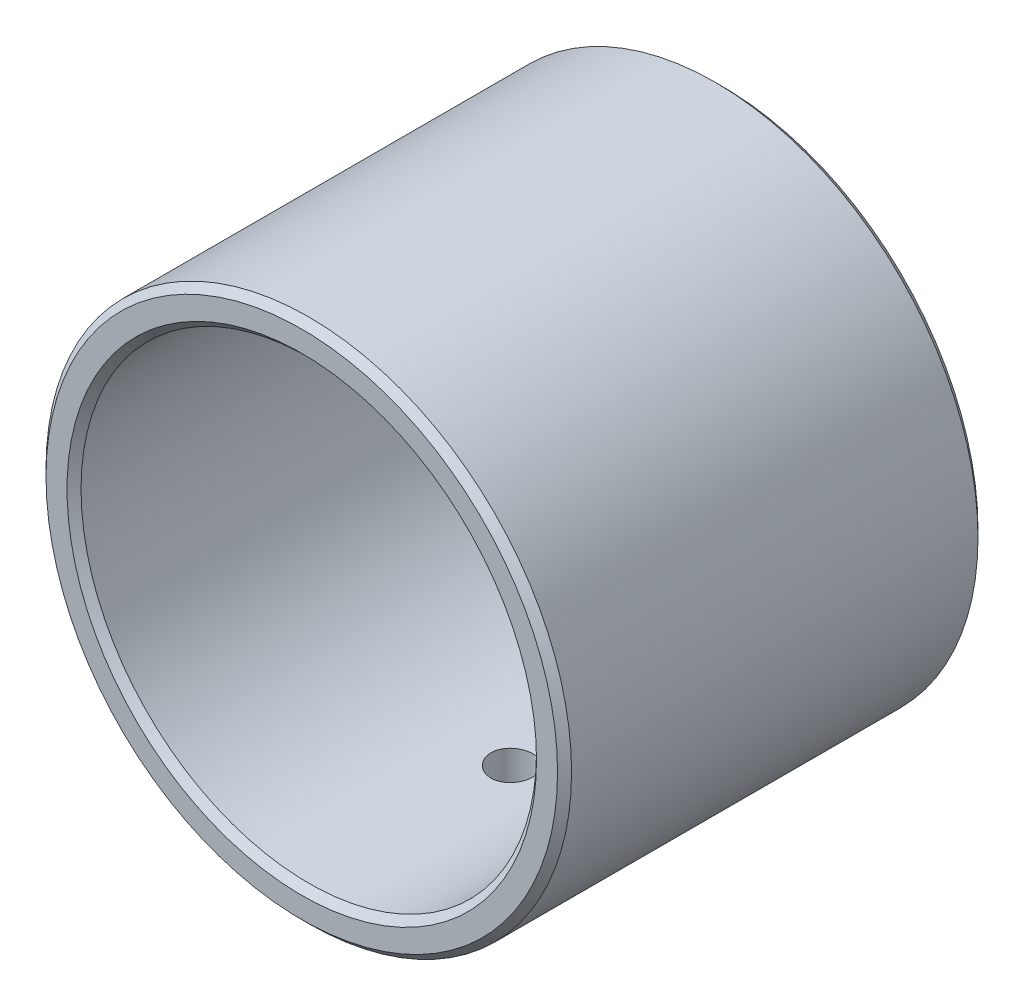
SolidWorks part; units mm, degrees
ref_plane "前视基准面" through (0, 0, 0) normal (0, 0, 1) x (1, 0, 0)
ref_plane "上视基准面" through (0, 0, 0) normal (0, 1, 0) x (1, 0, 0)
ref_plane "右视基准面" through (0, 0, 0) normal (1, 0, 0) x (0, 0, -1)
sketch "草图1" plane through (0, 0, 0) normal (0, 0, 1) x (1, 0, 0)
  circle A0 centre (0, 0) radius 32.5
  circle A1 centre (0, 0) radius 37.5
  dimension "D1" = 65
  dimension "D2" = 75
extrude "凸台-拉伸1" add sketch "草图1" along normal mid plane 60
chamfer "倒角1" distance 1 angle 45 4 edges at (37.5, 0, -30) (37.5, 0, 30) (32.5, 0, -30) (32.5, 0, 30)
sketch "草图2" plane through (0, 0, 0) normal (0, 1, 0) x (1, 0, 0)
  circle A0 centre (0, 0) radius 3
  dimension "D1" = 6
extrude "切除-拉伸1" cut sketch "草图2" against normal through all
